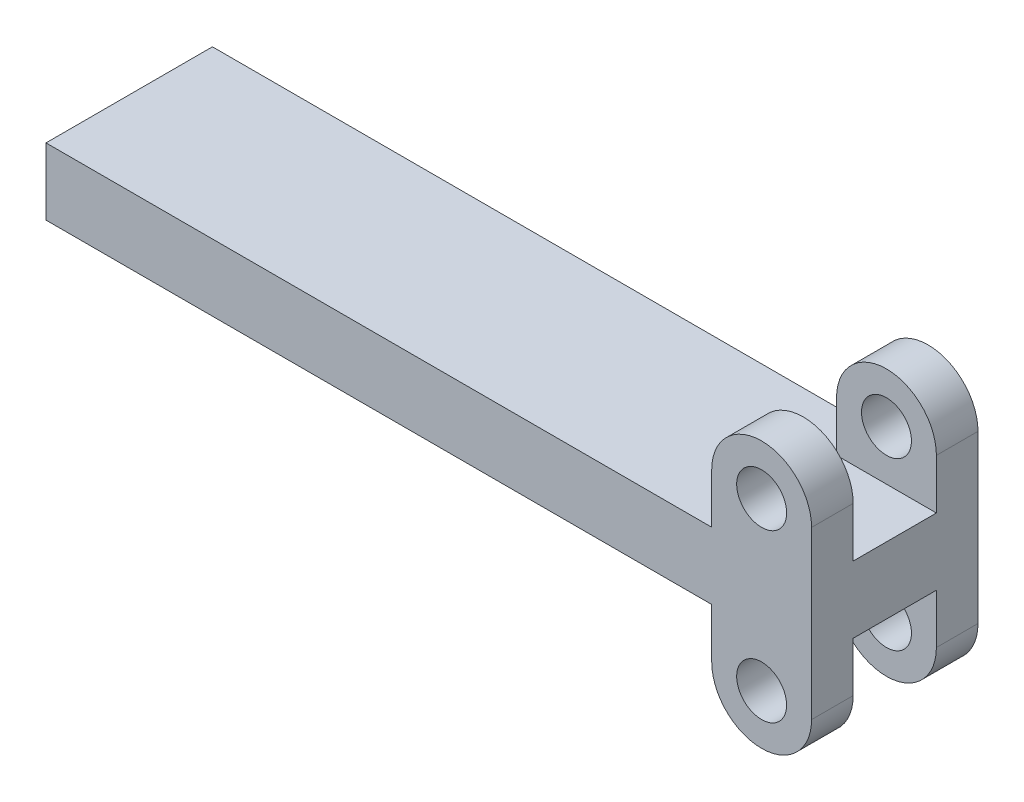
SolidWorks part; units mm, degrees
material "PUR"
ref_plane "Ön Düzlem" through (0, 0, 0) normal (0, 0, 1) x (1, 0, 0)
ref_plane "Üst Düzlem" through (0, 0, 0) normal (0, 1, 0) x (1, 0, 0)
ref_plane "Sağ Düzlem" through (0, 0, 0) normal (1, 0, 0) x (0, 0, -1)
sketch "Çizim1" plane through (0, 0, 0) normal (0, 0, 1) x (1, 0, 0)
  line L0 (-3, -1.0261) -> (-3, -11.0261)
  line L1 (3, -1.0261) -> (3, -11.0261)
  arc A0 (3, -1.0261) -> (-3, -1.0261) centre (0, -1.0261) ccw
  arc A1 (-3, -11.0261) -> (3, -11.0261) centre (0, -11.0261) ccw
  circle A2 centre (0, -1.0261) radius 1.5
  circle A3 centre (0, -11.0261) radius 1.5
  dimension "D1" = 6
  dimension "D3" = 3
  dimension "D2" = 10
extrude "Yükseklik-Ekstrüzyon1" add sketch "Çizim1" along normal mid plane 10
sketch "Çizim2" plane through (0, 0, 0) normal (0, 0, 1) x (1, 0, 0)
  line L5 (-3, -8.0437) -> (3, -8.0437)
  line L7 (0, -4.0261) -> (3, -4.0261)
  line L8 (-3, -1.0261) -> (-3, -11.0261)
  line L18 (3, -11.0261) -> (3, -1.0261)
  line L19 (-3, -1.0261) -> (-3, -4.0261)
  line L23 (3, -11.0261) -> (3, -8.0437)
  line L24 (3, -4.0261) -> (-3, -4.0261)
  line L25 (-3, -8.0437) -> (-3, -11.0261)
  line L26 (3, -4.0261) -> (3, -1.0261)
  line L27 (3, -1.0261) -> (3, -4.0261)
  arc A0 (3, -1.0261) -> (-3, -1.0261) centre (0, -1.0261) ccw
  arc A2 (3, -1.0261) -> (-3, -1.0261) centre (0, -1.0261) ccw
  arc A7 (-3, -11.0261) -> (3, -11.0261) centre (0, -11.0261) ccw
  arc A8 (3, -1.0261) -> (-3, -1.0261) centre (0, -1.0261) ccw
  arc A9 (-3, -11.0261) -> (3, -11.0261) centre (0, -11.0261) ccw
  point P0 (-0.3292, -4.0099)
  dimension "D1" = 0
extrude "Kes-Ekstrüzyon1" cut sketch "Çizim2" against normal mid plane 5 contours L26 A0 L19 L24 L7 | A9 L23 L5 L25
sketch "Çizim3" plane through (0, 0, 0) normal (0, 0, 1) x (1, 0, 0)
  line L0 (-3, -1.0261) -> (-3, -11.0261) construction
  line L1 (-43, -8.0361) -> (-3, -8.0361)
  line L2 (-43, -8.0361) -> (-43, -4.0161)
  line L3 (-43, -4.0161) -> (-3, -4.0161)
  line L4 (-3, -8.0361) -> (-3, -4.0161)
  line L5 (-43, -8.0361) -> (-3, -4.0161) construction
  line L6 (-43, -4.0161) -> (-3, -8.0361) construction
  line L7 (3, -11.0261) -> (3, -1.0261) construction
  point P0 (-23, -6.0261)
  point P10 (3, -6.0261)
  dimension "D1" = 4.02
  dimension "D2" = 40
extrude "Yükseklik-Ekstrüzyon7" add sketch "Çizim3" along normal mid plane 10
